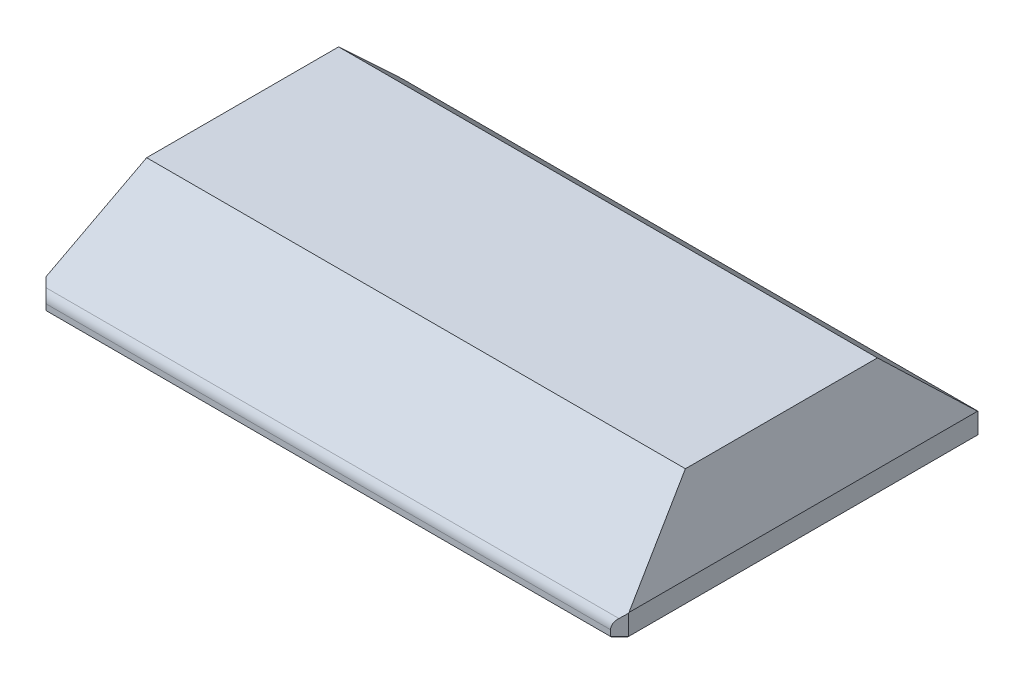
SolidWorks part; units mm, degrees
ref_plane "Front Plane" through (0, 0, 0) normal (0, 0, 1) x (1, 0, 0)
ref_plane "Top Plane" through (0, 0, 0) normal (0, 1, 0) x (1, 0, 0)
ref_plane "Right Plane" through (0, 0, 0) normal (1, 0, 0) x (0, 0, -1)
sketch "Sketch1" plane through (0, 0, 0) normal (0, 1, 0) x (1, 0, 0)
  line L1 (-65, -41) -> (65, -41)
  line L2 (-65, -41) -> (-65, 41)
  line L3 (-65, 41) -> (65, 41)
  line L4 (65, -41) -> (65, 41)
  line L5 (-65, -41) -> (65, 41) construction
  line L6 (-65, 41) -> (65, -41) construction
  point P0 (0, 0)
  dimension "D1" = 130
  dimension "D2" = 82
ref_plane "Plane1" through (0, 22, 0) normal (0, 1, 0) x (1, 0, 0)
sketch "Sketch2" plane through (0, 22, 0) normal (0, 1, 0) x (1, 0, 0)
  line L1 (-60, -23) -> (60, -23)
  line L2 (-60, -23) -> (-60, 23)
  line L3 (-60, 23) -> (60, 23)
  line L4 (60, -23) -> (60, 23)
  line L5 (-60, -23) -> (60, 23) construction
  line L6 (-60, 23) -> (60, -23) construction
  point P0 (0, 0)
  dimension "D1" = 46
  dimension "D2" = 120
extrude "Boss-Extrude1" add sketch "Sketch1" along normal blind 5
sketch "Sketch3" plane through (0, 5, 0) normal (0, 1, 0) x (1, 0, 0)
  line L4 (65, -41) -> (65, 41)
  line L5 (65, 41) -> (-65, 41)
  line L6 (-65, 41) -> (-65, -41)
  line L7 (-65, -41) -> (65, -41)
  line L8 (65, -41) -> (65, 41)
  line L9 (65, 41) -> (-65, 41)
  line L10 (-65, 41) -> (-65, -41)
  line L11 (-65, -41) -> (65, -41)
  dimension "D1" = 0
loft "Loft2" add profiles "Sketch3", "Sketch2"
chamfer "Chamfer1" distance 2 angle 45 4 edges at (-65, 2.5, 41) (65, 2.5, 41) (65, 2.5, -41) (-65, 2.5, -41)
sketch "Sketch4" plane through (0, 0, 0) normal (0, -1, 0) x (1, 0, 0)
  line L0 (0, 41) -> (0, -41) construction
  line L1 (-63, 41) -> (63, 41) construction
  line L2 (63, -41) -> (-63, -41) construction
  line L3 (-40, -37.5) -> (40, -37.5) construction
  circle A0 centre (40, -37.5) radius 1.2
  circle A1 centre (-40, -37.5) radius 1.2
  point P9 (0, -37.5)
  dimension "D3" = 2.4
  dimension "D1" = 3.5
  dimension "D2" = 80
extrude "Cut-Extrude1" cut sketch "Sketch4" against normal blind 4
sketch "Sketch5" plane through (0, 0, 0) normal (0, -1, 0) x (1, 0, 0)
  line L1 (-57, -20) -> (57, -20)
  line L2 (-57, -20) -> (-57, 20)
  line L3 (-57, 20) -> (57, 20)
  line L4 (57, -20) -> (57, 20)
  line L5 (-57, -20) -> (57, 20) construction
  line L6 (-57, 20) -> (57, -20) construction
  point P0 (0, 0)
  dimension "D1" = 40
  dimension "D2" = 114
extrude "Cut-Extrude2" cut sketch "Sketch5" against normal offset from surface (21 mm away) 1 up to face at (0, 22, 0)
mirror "Mirror1" about plane through (0, 0, 0) normal (0, 0, 1) of "Cut-Extrude1"
sketch "Sketch6" plane through (0, 0, 0) normal (0, -1, 0) x (1, 0, 0)
  line L0 (-57, 20) -> (-57, -20) construction
  line L1 (-59, -28) -> (59, -28)
  line L2 (-59, -28) -> (-59, 28)
  line L3 (-59, 28) -> (59, 28)
  line L4 (59, -28) -> (59, 28)
  line L5 (-59, -28) -> (59, 28) construction
  line L6 (-59, 28) -> (59, -28) construction
  line L7 (-57, 20) -> (57, 20) construction
  point P0 (0, 0)
  dimension "D1" = 2
  dimension "D2" = 8
extrude "Cut-Extrude3" cut sketch "Sketch6" against normal blind 12
ref_plane "Plane2" through (0, 4, 0) normal (0, -1, 0) x (-1, 0, 0)
sketch "Sketch8" plane through (0, 4, 0) normal (0, -1, 0) x (-1, 0, 0)
  line L0 (0, 28) -> (0, -41) construction
  line L1 (-59, 28) -> (-52, 28)
  line L2 (-59, 28) -> (-59, 21)
  line L3 (-59, 21) -> (-52, 21)
  line L4 (-52, 28) -> (-52, 21)
  line L5 (59, 28) -> (-59, 28) construction
  line L6 (63, -41) -> (-63, -41) construction
  line L7 (59, 0) -> (-59, 0) construction
  line L8 (59, -28) -> (59, 28) construction
  line L9 (-59, 28) -> (-59, -28) construction
  line L10 (-52, -28) -> (-52, -21)
  line L11 (-59, -21) -> (-52, -21)
  line L12 (-59, -28) -> (-59, -21)
  line L13 (-59, -28) -> (-52, -28)
  line L14 (59, -28) -> (52, -28)
  line L15 (59, -28) -> (59, -21)
  line L16 (59, -21) -> (52, -21)
  line L17 (52, -28) -> (52, -21)
  line L18 (52, 28) -> (52, 21)
  line L19 (59, 21) -> (52, 21)
  line L20 (59, 28) -> (59, 21)
  line L21 (59, 28) -> (52, 28)
  dimension "D1" = 7
extrude "Boss-Extrude2" add sketch "Sketch8" against normal up to surface (8 mm away) up to face at (0, 12, 0)
sketch "Sketch9" plane through (0, 4, 0) normal (0, -1, 0) x (1, 0, 0)
  line L0 (0, 28) -> (0, -41) construction
  line L1 (52, 28) -> (-52, 28) construction
  line L2 (63, -41) -> (-63, -41) construction
  line L3 (59, 0) -> (-59, 0) construction
  line L4 (59, -28) -> (59, 28) construction
  line L5 (-59, 28) -> (-59, -28) construction
  line L6 (-59, 28) -> (-52, 21) construction
  circle A0 centre (-55.5, 24.5) radius 2.1
  circle A1 centre (55.5, 24.5) radius 2.1
  circle A2 centre (55.5, -24.5) radius 2.1
  circle A3 centre (-55.5, -24.5) radius 2.1
  dimension "D1" = 4.2
extrude "Cut-Extrude4" cut sketch "Sketch9" against normal up to surface (8 mm away) up to face at (0, 12, 0)
sketch "Sketch10" plane through (0, 12, 0) normal (0, -1, 0) x (1, 0, 0)
  line L0 (-59, 28) -> (-59, -28) construction
  line L1 (-57, 20) -> (-59, 20)
  line L2 (-57, 20) -> (-57, -20)
  line L3 (-57, -20) -> (-59, -20)
  line L4 (-59, 20) -> (-59, -20)
  line L5 (59, -21) -> (59, 21) construction
  line L6 (57, -20) -> (59, -20)
  line L7 (57, -20) -> (57, 20)
  line L8 (57, 20) -> (59, 20)
  line L9 (59, -20) -> (59, 20)
  line L10 (-57, 20) -> (57, 20) construction
  line L11 (-57, -20) -> (57, -20) construction
extrude "Cut-Extrude5" cut sketch "Sketch10" against normal up to surface (9 mm away) up to face at (0, 21, 0)
sketch "Sketch11" plane through (0, 0, 0) normal (1, 0, 0) x (0, 0, -1)
  line L0 (21, 22) -> (41, 3)
  line L1 (-23, 22) -> (23, 22) construction
  line L2 (41, 5) -> (41, 0) construction
  line L3 (41, 3) -> (41, 5)
  line L4 (41, 5) -> (23, 22)
  line L5 (23, 22) -> (21, 22)
  line L6 (20, 21) -> (20, 12) construction
  line L7 (0, 22) -> (0, 0) construction
  line L8 (-23, 22) -> (-21, 22)
  line L9 (-41, 5) -> (-23, 22)
  line L10 (-41, 3) -> (-41, 5)
  line L11 (-21, 22) -> (-41, 3)
  dimension "D1" = 1
  dimension "D2" = 2
extrude "Cut-Extrude6" cut sketch "Sketch11" against normal through all both and the other way through all
sketch "Sketch12" plane through (0, 0, 0) normal (1, 0, 0) x (0, 0, -1)
  line L0 (-21, 22) -> (21, 22) construction
  line L1 (-41, 23.6) -> (41, 23.6)
  line L2 (-41, 23.6) -> (-41, 21.6)
  line L3 (-41, 21.6) -> (41, 21.6)
  line L4 (41, 23.6) -> (41, 21.6)
  dimension "D1" = 0.4
  dimension "D2" = 2
extrude "Cut-Extrude7" cut sketch "Sketch12" against normal through all both and the other way through all
fillet "Fillet1" radius 3 2 edges at (0, 3, 41) (0, 3, -41)
chamfer "Chamfer2" distance 0.4 angle 45 8 edges at (-64, 0, -40) (-65, 0, 0) (-64, 0, 40) (0, 0, 41) (64, 0, 40) (65, 0, 0) (64, 0, -40) (0, 0, -41)
